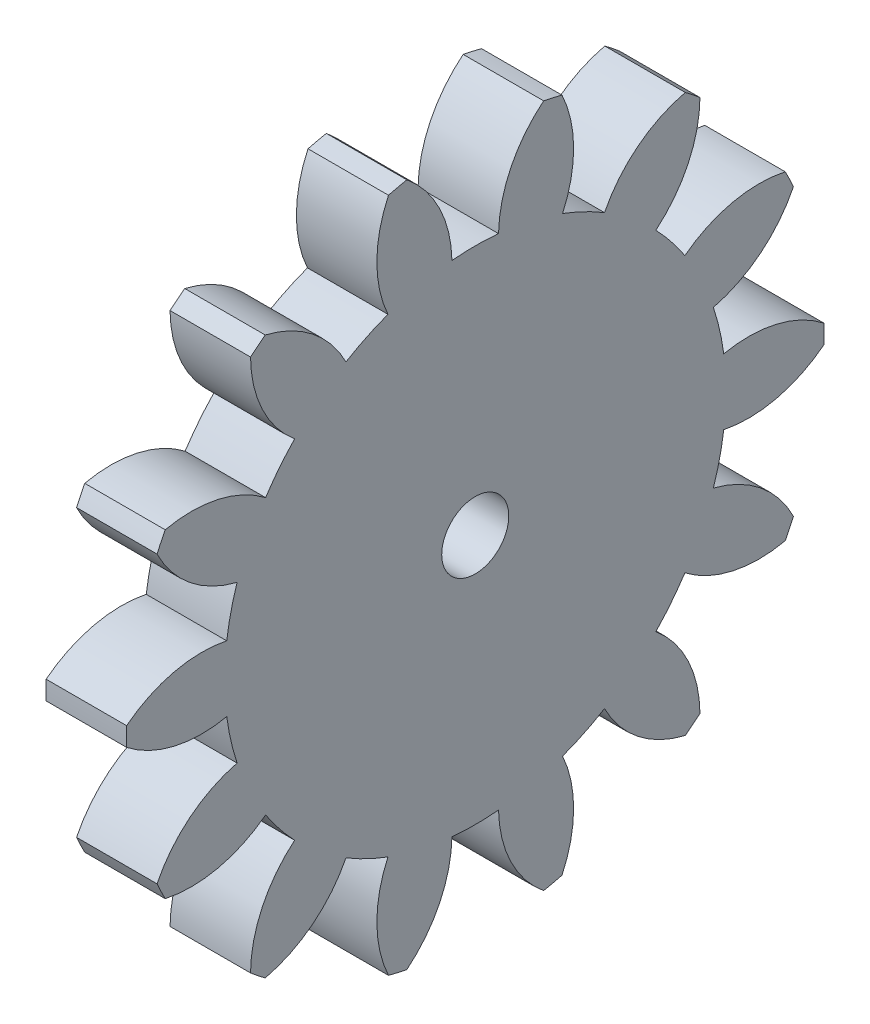
SolidWorks part; units mm, degrees
ref_plane "Plane1" through (0, 0, 0) normal (0, 0, 1) x (1, 0, 0)
ref_plane "Plane2" through (0, 0, 0) normal (0, 1, 0) x (1, 0, 0)
ref_plane "Plane3" through (0, 0, 0) normal (1, 0, 0) x (0, 0, -1)
other "Configuration Table"
sketch "HoldingSke" plane through (0, 0, 0) normal (0, 1, 0) x (1, 0, 0)
  line L0 (0, 0) -> (0.1493, -0.0372)
  line L1 (-15, 0) -> (100, 0) construction
  line L2 (0, 0) -> (-2.1039, 2.3779)
  line L3 (0, 0) -> (-11.863, 4.5341)
  line L4 (0, 0) -> (8.3795, 2.0892)
  line L5 (0, 0) -> (-46.8476, -17.4728)
  line L6 (0, 0) -> (-9.9476, -6.7116)
  line L7 (-2.1039, 2.3779) -> (8.6586, 51.2059)
  line L8 (-76.2, 54.61) -> (-74.4, 54.61)
  line L9 (-71.009, 38.7566) -> (-53.1078, 45.2721)
  line L10 (-76.2, 71.12) -> (104.1128, 71.12)
  line L11 (0, 0) -> (-12, 0)
  line L12 (-76.2, 101.6) -> (-75.981, 101.6)
  line L13 (24.9733, 27.94) -> (52.9518, 28.4284)
  line L14 (24.9733, 27.94) -> (24.9743, 27.94)
  line L15 (24.9733, 27.94) -> (100.4006, 29.5858)
  line L16 (-63.627, -6.5) -> (-12.827, -6.5)
  circle A0 centre (0, 0) radius 5
  circle A1 centre (0, 0) radius 37.374
  circle A2 centre (0, 0) radius 37.5
  circle A3 centre (0, 0) radius 5
  dimension "MHD" = 74.748
  dimension "Hub_dia" = 75
  dimension "Bore" = 10
  dimension "MBD" = 10
  dimension "Num_teeth" = 14
  dimension "Pitch" = 0.1538
  dimension "Overall_len" = 50
  dimension "Show_teeth" = 14
  dimension "Thickness" = 12
  dimension "OAL" = 50.0001
  dimension "T_dim" = 1.8
  dimension "Ap" = 20
  dimension "H" = 19.05
  dimension "Pitch_radius" = 180.3128
  dimension "Width" = 12
  dimension "Backlash" = 0.219
  dimension "Addendum_fac" = 1
  dimension "Dedendum_fac" = 1.25
  dimension "Clearance_fac" = 0.25
  dimension "Dedendum_add" = 0.001
  dimension "Module" = 6.5
sketch "BasProSke" plane through (0, 0, 0) normal (0, 1, 0) x (1, 0, 0)
  line L0 (-10, 0) -> (60, 0) construction
  line L1 (0, 0) -> (0, 52)
  line L2 (0, 0) -> (12, 0)
  line L3 (12, 0) -> (12, 52)
  line L4 (12, 52) -> (0, 52)
  dimension "Thickness" = 12
  dimension "Diameter" = 104
revolve "Base-Revolve" add sketch "BasProSke" angle 360 about L0
sketch "TooCutSke" plane through (0, 0, 0) normal (1, 0, 0) x (0, 0, -1)
  line L1 (0, 0) -> (0, 107) construction
  line L2 (0, 0) -> (-5.4773, 45.1691) construction
  line L3 (0, 0) -> (-20.1406, 88.2416) construction
  line L4 (-5.4773, 45.1691) -> (-10.0703, 44.1208) construction
  arc A0 (3.4724, 37.2123) -> (-3.4724, 37.2123) centre (0, 0) ccw
  arc A1 (10.2255, 51.0106) -> (-10.2255, 51.0106) centre (0, 0) ccw
  circle A2 centre (0, 0) radius 45.5 construction
  circle A3 centre (0, 0) radius 42.756 construction
  arc A4 (-3.4724, 37.2123) -> (-10.2255, 51.0106) centre (-21.6689, 36.8583) ccw
  arc A5 (10.2255, 51.0106) -> (3.4724, 37.2123) centre (21.6689, 36.8583) ccw
  dimension "Root_dia" = 74.748
  dimension "Overcut_dia" = 104.0508
  dimension "Pitch_dia" = 91
  dimension "Base_dia" = 85.512
  dimension "Flank_rad" = 18.2
  dimension "Half_ang" = 12.857
  dimension "Half_CT" = 4.7111
extrude "ToothCut" cut sketch "TooCutSke" along normal through all
fillet "Breaks" [suppressed] radius 0.13
fillet "RootFillets" [suppressed] radius 1.626
pattern_circular "TeethCuts" count 14 every 25.714 about axis through (-10, 0, 0) along (1, 0, 0) of "ToothCut", "RootFillets", "Breaks"
sketch "HubNeaOneSke" plane through (0, 0, 0) normal (-1, 0, 0) x (0, 0, 1)
  circle A0 centre (0, 0) radius 37.374
  dimension "Diameter" = 74.748
extrude "HubNearOne" [suppressed] add sketch "HubNeaOneSke" along normal blind 38.0001
sketch "HubNeaBotSke" plane through (0, 0, 0) normal (-1, 0, 0) x (0, 0, 1)
  circle A0 centre (0, 0) radius 37.374
  dimension "Diameter" = 74.748
extrude "HubNearBoth" [suppressed] add sketch "HubNeaBotSke" along normal blind 19
ref_plane "FarPln" through (12, 0, 0) normal (1, 0, 0) x (0, 0, -1)
sketch "HubFarSke" plane through (12, 0, 0) normal (1, 0, 0) x (0, 0, -1)
  circle A0 centre (0, 0) radius 37.374
  dimension "Diameter" = 74.748
extrude "HubFar" [suppressed] add sketch "HubFarSke" along normal blind 19
sketch "BorSke" plane through (0, 0, 0) normal (1, 0, 0) x (0, 0, -1)
  circle A0 centre (0, 0) radius 5
  dimension "Diameter" = 10
extrude "Bore" cut sketch "BorSke" along normal mid plane 100.0001
sketch "KeySke" plane through (0, 0, 0) normal (1, 0, 0) x (0, 0, -1)
  line L0 (-2, 0) -> (-2, 6.8)
  line L1 (-2, 6.8) -> (2, 6.8)
  line L2 (2, 6.8) -> (2, 0)
  line L3 (0, 0) -> (0, 34) construction
  line L4 (-2, 0) -> (2, 0)
  dimension "Offset" = 6.8
  dimension "Width" = 4
extrude "Keyway" [suppressed] cut sketch "KeySke" along normal mid plane 100.0001
pattern_circular "Keyway2" [suppressed] count 2 every 90 about axis through (-10, 0, 0) along (1, 0, 0)
sketch "草图1" plane through (0, 0, 0) normal (-1, 0, 0) x (0, 0, 1)
  circle A0 centre (0, 0) radius 5 construction
  circle A1 centre (0, 0) radius 5 construction
  circle A2 centre (0, 0) radius 29.1568 construction
sketch "草图2" plane through (0, 0, 0) normal (-1, 0, 0) x (0, 0, 1)
  circle A0 centre (0, 0) radius 5 construction
  circle A1 centre (0, 0) radius 5 construction
  circle A2 centre (0, 0) radius 37.4818 construction
equation "' \"Module@HoldingSke\" = 6.35"
equation "' \"Num_teeth@HoldingSke\" = 12"
equation "' \"Ap@HoldingSke\" =  20"
equation "' \"Ap@HoldingSke\" = 20"
equation "' \"Width@HoldingSke\" = 0.5 * 25.4"
equation "' \"Hub_dia@HoldingSke\"= 1 * 25.4"
equation "' \"Hub_dia@HoldingSke\" = 1 * 25.4"
equation "' \"Overall_len@HoldingSke\" = 1.0 * 25.4"
equation "' \"Bore@HoldingSke\" = 0.75 * 25.4"
equation "' \"T_dim@HoldingSke\" = 0.1 * 25.4"
equation "' \"Width@KeySke\" = 0.25 * 25.4"
equation "' \"Show_teeth@HoldingSke\" = 13"
equation "' \"Backlash@HoldingSke\" = 0.009 * 25.4"
equation "' \"Addendum_fac@HoldingSke\" = 1.0"
equation "' \"Dedendum_fac@HoldingSke\" = 1.25"
equation "' \"Dedendum_add@HoldingSke\" = 0.00005 * 25.4"
equation "' \"Clearance_fac@HoldingSke\" = 0.25"
equation "\"Pitch@HoldingSke\" = 1 / \"Module@HoldingSke\""
equation "\"Overcut_dia@TooCutSke\" = (\"Num_teeth@HoldingSke\" + 2 * \"Addendum_fac@HoldingSke\") / \"Pitch@HoldingSke\" + 0.002 * 25.4"
equation "\"Pitch_dia@TooCutSke\" = \"Num_teeth@HoldingSke\" / \"Pitch@HoldingSke\""
equation "\"Base_dia@TooCutSke\" = \"Num_teeth@HoldingSke\" / \"Pitch@HoldingSke\" * cos((\"Ap@HoldingSke\"  * 3.14159265 / 180))"
equation "\"Root_dia@TooCutSke\" = (\"Num_teeth@HoldingSke\" + 2) / \"Pitch@HoldingSke\" - 2 * (\"Addendum_fac@HoldingSke\" + \"Dedendum_fac@HoldingSke\") / \"Pitch@HoldingSke\" - \"Dedendum_add@HoldingSke\" * 2"
equation "\"Half_ang@TooCutSke\" = 180 / \"Num_teeth@HoldingSke\""
equation "\"Half_CT@TooCutSke\" = \"Num_teeth@HoldingSke\" / \"Pitch@HoldingSke\" * sin((3.14159265 / 2 / \"Num_teeth@HoldingSke\")) / 2 - 7 * \"Backlash@HoldingSke\" / 4"
equation "\"Flank_rad@TooCutSke\" = \"Num_teeth@HoldingSke\" / \"Pitch@HoldingSke\" / 5"
equation "\"Radius@RootFillets\" = \"Clearance_fac@HoldingSke\" / \"Pitch@HoldingSke\" + \"Dedendum_add@HoldingSke\""
equation "\"Break_rad@Breaks\" = 0.02 / \"Pitch@HoldingSke\""
equation "\"Thickness@HoldingSke\" = \"Width@HoldingSke\""
equation "\"OAL@HoldingSke\" = \"Thickness@HoldingSke\""
equation "\"MHD@HoldingSke\" = (\"Num_teeth@HoldingSke\" + 2) / \"Pitch@HoldingSke\" - 2 * (\"Addendum_fac@HoldingSke\" + \"Dedendum_fac@HoldingSke\")  / \"Pitch@HoldingSke\" - \"Dedendum_add@HoldingSke\" * 2"
equation "\"MBD@HoldingSke\" = (\"Num_teeth@HoldingSke\" + 2) / \"Pitch@HoldingSke\" - 2 * (\"Addendum_fac@HoldingSke\" + \"Dedendum_fac@HoldingSke\")  / \"Pitch@HoldingSke\" - \"Dedendum_add@HoldingSke\" * 2 - 0.002 * 25.4"
equation "\"MHD@HoldingSke\" = ((sgn( \"MHD@HoldingSke\" - \"Hub_dia@HoldingSke\" )-1)*( \"MHD@HoldingSke\" - \"Hub_dia@HoldingSke\" ))/-2+ \"Hub_dia@HoldingSke\""
equation "\"MBD@HoldingSke\" = ((sgn( \"MBD@HoldingSke\" - \"Bore@HoldingSke\" )-1)*( \"MBD@HoldingSke\" - \"Bore@HoldingSke\" ))/-2+ \"Bore@HoldingSke\""
equation "\"OAL@HoldingSke\" = ((sgn( \"OAL@HoldingSke\" - \"Overall_len@HoldingSke\" )+1)*( \"OAL@HoldingSke\" - \"Overall_len@HoldingSke\" ))/2 + \"Overall_len@HoldingSke\" + 0.000002 * 25.4"
equation "\"Num_teeth@TeethCuts\" = int( \"Show_teeth@HoldingSke\" ) + 1"
equation "\"Num_teeth@TeethCuts\" = ((sgn( \"Num_teeth@TeethCuts\" - \"Num_teeth@HoldingSke\" )-1)*( \"Num_teeth@TeethCuts\" - \"Num_teeth@HoldingSke\" ))/-2+ \"Num_teeth@HoldingSke\""
equation "\"Num_teeth@TeethCuts\" = ((sgn( \"Num_teeth@TeethCuts\" - 2.0)+1)*( \"Num_teeth@TeethCuts\" - 2.0))/2 +2.0"
equation "\"Angle@TeethCuts\" = 360.0 / \"Num_teeth@HoldingSke\""
equation "\"Diameter@BasProSke\" = (\"Num_teeth@HoldingSke\" + 2 * \"Addendum_fac@HoldingSke\") / \"Pitch@HoldingSke\""
equation "\"Thickness@BasProSke\"  = \"Thickness@HoldingSke\""
equation "' \"Fillet_rad@BasProSke\" =  \"Thickness@HoldingSke\" * 0.05"
equation "' \"Fillet_rad@BasProSke\" = \"Thickness@HoldingSke\" * 0.05"
equation "\"MHD@HoldingSke\" = ((sgn( \"MHD@HoldingSke\" - \"Root_dia@TooCutSke\" )-1)*( \"MHD@HoldingSke\" - \"Root_dia@TooCutSke\" ))/-2+ \"Root_dia@TooCutSke\""
equation "\"Diameter@HubNeaOneSke\" = \"MHD@HoldingSke\""
equation "\"Length@HubNearOne\" = \"OAL@HoldingSke\" - \"Thickness@BasProSke\""
equation "\"Diameter@HubNeaBotSke\" = \"MHD@HoldingSke\""
equation "\"Length@HubNearBoth\" = ( \"OAL@HoldingSke\" - \"Thickness@BasProSke\" ) / 2.0"
equation "\"Thickness@FarPln\" = \"Thickness@BasProSke\""
equation "\"Diameter@HubFarSke\" = \"MHD@HoldingSke\""
equation "\"Length@HubFar\" = ( \"OAL@HoldingSke\" - \"Thickness@BasProSke\" ) / 2.0"
equation "\"Diameter@BorSke\" = \"MBD@HoldingSke\""
equation "\"D1@Bore\" = \"OAL@HoldingSke\" * 2.0"
equation "\"D1@Keyway\" = \"OAL@HoldingSke\" * 2.0"
equation "\"Offset@KeySke\" = \"T_dim@HoldingSke\" + \"MBD@HoldingSke\" / 2.0"
